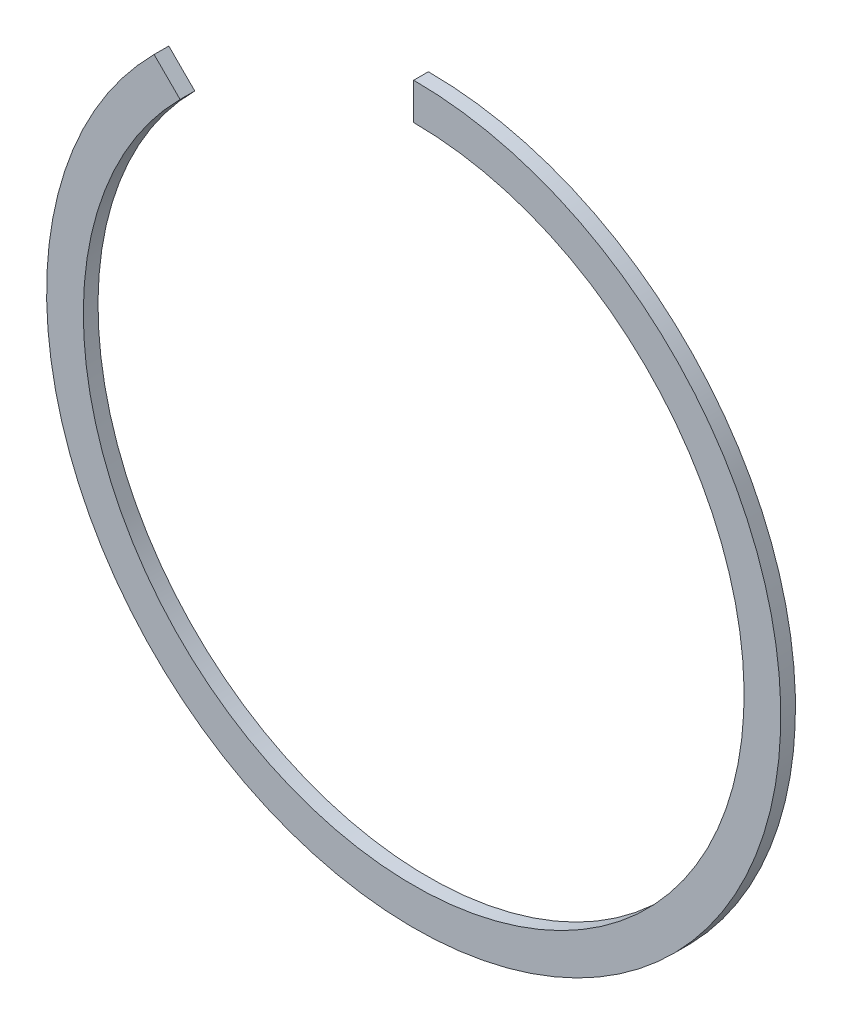
SolidWorks part; units mm, degrees
ref_plane "Front Plane" through (0, 0, 0) normal (0, 0, 1) x (1, 0, 0)
ref_plane "Top Plane" through (0, 0, 0) normal (0, 1, 0) x (1, 0, 0)
ref_plane "Right Plane" through (0, 0, 0) normal (1, 0, 0) x (0, 0, -1)
sketch "Sketch1" plane through (0, 0, 0) normal (0, 0, 1) x (1, 0, 0)
  line L0 (0, 22.5) -> (0, 25)
  line L1 (0, 0) -> (0, 146.833) construction
  line L2 (0, 0) -> (-17.6777, 17.6777) construction
  line L3 (-17.6777, 17.6777) -> (-15.9099, 15.9099)
  circle A0 centre (0, 0) radius 25
  circle A1 centre (0, 0) radius 22.5
  dimension "D1" = 50
  dimension "D2" = 45
extrude "Boss-Extrude1" add sketch "Sketch1" along normal blind 1 contours A1 L3 A0 L0
